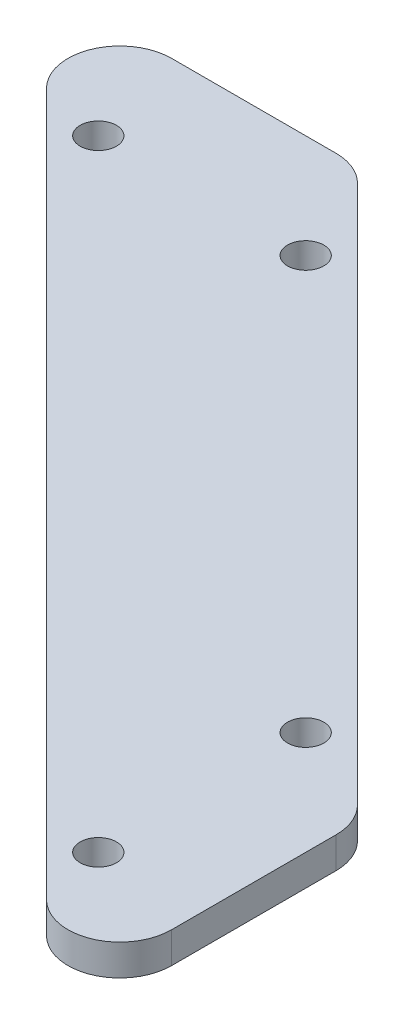
SolidWorks part; units mm, degrees
ref_plane "Front Plane" through (0, 0, 0) normal (0, 0, 1) x (1, 0, 0)
ref_plane "Top Plane" through (0, 0, 0) normal (0, 1, 0) x (1, 0, 0)
ref_plane "Right Plane" through (0, 0, 0) normal (1, 0, 0) x (0, 0, -1)
sketch "Sketch1" plane through (0, 0, 0) normal (0, 1, 0) x (1, 0, 0)
  line L0 (0, 0) -> (-84.8528, 84.8528)
  line L1 (-84.8528, 84.8528) -> (-54.8528, 84.8528)
  line L2 (-54.8528, 84.8528) -> (0, 30)
  line L3 (0, 30) -> (0, 0)
  dimension "D1" = 30
  dimension "D2" = 120
extrude "Boss-Extrude1" add sketch "Sketch1" along normal blind 3
sketch "Sketch2" plane through (0, 3, 0) normal (0, 1, 0) x (1, 0, 0)
  line L2 (-79.8528, 84.8528) -> (0, 5) construction
  line L3 (-54.8528, 84.8528) -> (-84.8528, 84.8528) construction
  line L4 (0, 0) -> (0, 30) construction
  circle A1 centre (-69.8528, 74.8528) radius 1.75
  circle A2 centre (-49.8528, 74.8528) radius 1.75
  circle A3 centre (-10, 15) radius 1.75
  circle A4 centre (-10, 35) radius 1.75
  dimension "D1" = 10
  dimension "D3" = 3.5
  dimension "D5" = 3.5
  dimension "D7" = 3.5
  dimension "D9" = 3.5
  dimension "D2" = 5
  dimension "D4" = 20
  dimension "D6" = 5
  dimension "D8" = 10
  dimension "D10" = 20
extrude "Cut-Extrude1" cut sketch "Sketch2" against normal through all
fillet "Fillet2" radius 5 4 edges at (0, 1.5, 0) (0, 1.5, -30) (-54.8528, 1.5, -84.8528) (-84.8528, 1.5, -84.8528)
